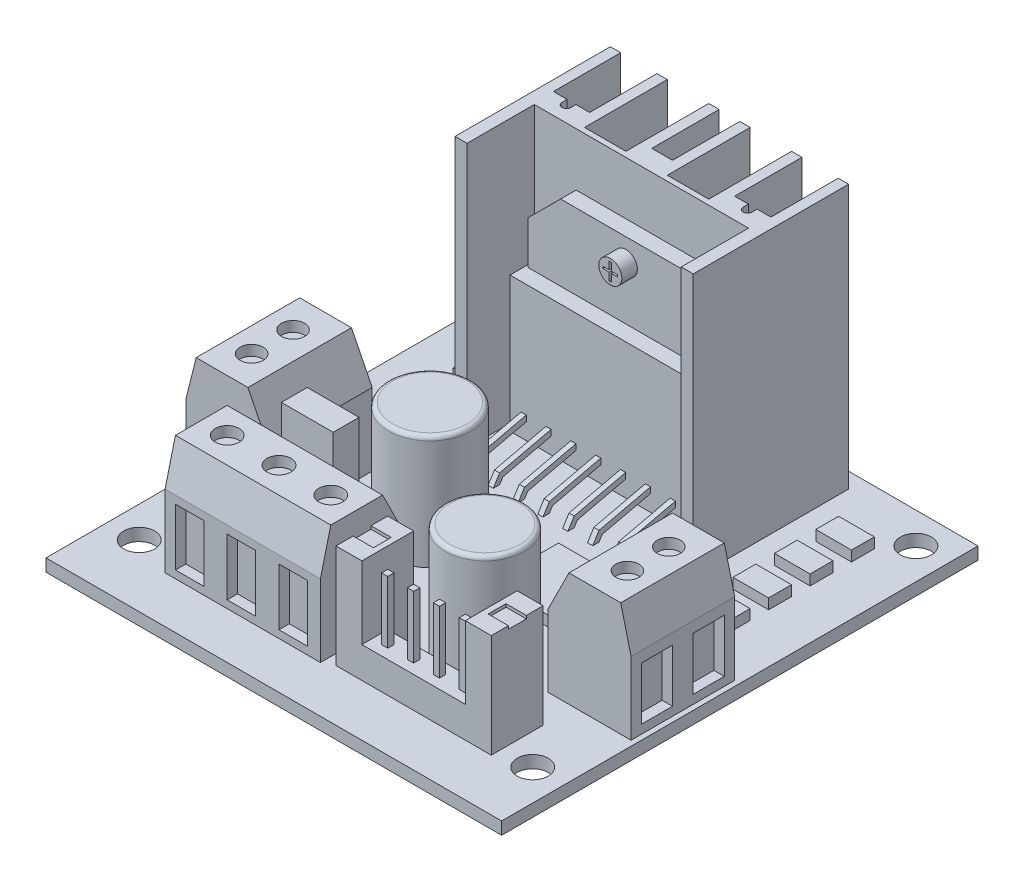
SolidWorks part; units mm, degrees
ref_plane "Alzado" through (0, 0, 0) normal (0, 0, 1) x (1, 0, 0)
ref_plane "Planta" through (0, 0, 0) normal (0, 1, 0) x (1, 0, 0)
ref_plane "Vista lateral" through (0, 0, 0) normal (1, 0, 0) x (0, 0, -1)
sketch "Croquis1" plane through (0, 0, 0) normal (0, 1, 0) x (1, 0, 0)
  line L0 (0, 0) -> (0, -13.9833) construction
  line L1 (-22, 23) -> (22, 23)
  line L2 (-22, 23) -> (-22, -23)
  line L3 (-22, -23) -> (22, -23)
  line L4 (22, 23) -> (22, -23)
  line L5 (-22, 23) -> (22, -23) construction
  line L6 (-22, -23) -> (22, 23) construction
  circle A0 centre (-19, 20) radius 1.5
  circle A1 centre (-19, -17) radius 1.5
  circle A2 centre (19, -17) radius 1.5
  circle A3 centre (19, 20) radius 1.5
  point P0 (0, 0)
  dimension "D3" = 3
  dimension "D5" = 6
  dimension "D1" = 44
  dimension "D2" = 46
  dimension "D4" = 3
  dimension "D6" = 3
extrude "Saliente-Extruir1" add sketch "Croquis1" along normal blind 1.2
sketch "Croquis2" plane through (0, 1.2, 0) normal (0, 1, 0) x (1, 0, 0)
  line L0 (-11, 21.5) -> (-11, 15)
  line L1 (-12, 21.5) -> (-11, 21.5)
  line L2 (-12, 21.5) -> (-12, 6.5)
  line L3 (-12, 6.5) -> (-10.8432, 6.5)
  line L4 (11, 21.5) -> (11, 6.5)
  line L5 (-12, 21.5) -> (11, 6.5) construction
  line L6 (-12, 6.5) -> (11, 21.5) construction
  line L7 (-7.5, 21.5) -> (-7.5, 15)
  line L8 (-6.5, 21.5) -> (-6.5, 13.5)
  line L9 (-2.5, 21.5) -> (-2.5, 13.5)
  line L10 (-1.5, 21.5) -> (-1.5, 15)
  line L11 (-11, 15) -> (-9.6769, 15)
  line L12 (-6.5, 13.5) -> (-2.5, 13.5)
  line L13 (9.8432, 6.5) -> (11, 6.5)
  line L14 (-7.5, 21.5) -> (-7.5, 11.9163) construction
  line L15 (-6.5, 15) -> (-6.0594, 15)
  line L16 (-6.5, 21.5) -> (-6.5, 11.9163) construction
  line L17 (-8.8231, 15) -> (-8.8231, 14.5062)
  line L18 (-9.6769, 15) -> (-9.6769, 14.5062)
  line L19 (-8.8231, 15) -> (-7.5, 15)
  line L20 (-1.5, 21.5) -> (-1.5, 11.9163) construction
  line L21 (-2.5, 21.5) -> (-2.5, 11.9163) construction
  line L22 (-0.5, 14) -> (-0.5, 10.3568) construction
  line L23 (0.5, 21.5) -> (0.5, 15)
  line L24 (1.5, 21.5) -> (1.5, 13.5)
  line L25 (5.5, 13.5) -> (1.5, 13.5)
  line L26 (5.5, 21.5) -> (5.5, 13.5)
  line L27 (8.6769, 15) -> (8.6769, 14.5062)
  line L28 (7.8231, 15) -> (7.8231, 14.5062)
  line L29 (7.8231, 15) -> (6.5, 15)
  line L30 (10, 15) -> (8.6769, 15)
  line L31 (6.5, 21.5) -> (6.5, 15)
  line L32 (10, 21.5) -> (10, 15)
  line L33 (-0.5, 6.5) -> (-0.5, 10) construction
  line L34 (0.5, 15) -> (-1.5, 15)
  line L35 (-10.8432, 7.0064) -> (-10.8432, 6.5)
  line L36 (-10.8432, 12.9936) -> (9.8432, 12.9936)
  line L37 (-10.8432, 12.9936) -> (-10.8432, 7.0064)
  line L39 (9.8432, 12.9936) -> (9.8432, 7.0064)
  line L40 (-10.8432, 12.9936) -> (9.8432, 7.0064) construction
  line L41 (-10.8432, 7.0064) -> (9.8432, 12.9936) construction
  line L42 (9.8432, 7.0064) -> (9.8432, 6.5)
  line L43 (-7.5, 21.5) -> (-6.5, 21.5)
  line L44 (-2.5, 21.5) -> (-1.5, 21.5)
  line L45 (5.5, 21.5) -> (6.5, 21.5)
  line L46 (0.5, 21.5) -> (1.5, 21.5)
  line L47 (10, 21.5) -> (11, 21.5)
  line L48 (22, -23) -> (22, 23) construction
  line L49 (22, 23) -> (-22, 23) construction
  arc A1 (-9.6769, 14.5062) -> (-8.8231, 14.5062) centre (-9.25, 14.5062) ccw
  arc A2 (8.6769, 14.5062) -> (7.8231, 14.5062) centre (8.25, 14.5062) cw
  point P0 (-0.5, 14)
  point P24 (-5.9103, 15.0438)
  dimension "D1" = 15
  dimension "D2" = 23
  dimension "D3" = 1
  dimension "D4" = 3.5
  dimension "D8" = 6.5
  dimension "D9" = 8
  dimension "D10" = 3.5
  dimension "D11" = 11
  dimension "D12" = 1.5
  dimension "D5" = 1
  dimension "D6" = 4
  dimension "D7" = 1
extrude "Saliente-Extruir2" add sketch "Croquis2" along normal blind 25.5 contours L27 A2 L28 L29 L31 L45 L26 L25 L24 L46 L23 L34 L10 L44 L9 L12 L8 L43 L7 L19 L17 A1 L18 L11 L0 L1 L2 L3 L35 L37 L36 L39 L42 L13 L4 L47 L32 L30
sketch "Croquis3" plane through (0, 0, -12.9936) normal (0, 0, 1) x (1, 0, 0)
  line L0 (-10.8432, 7.7335) -> (9.8432, 7.7335)
  line L1 (-10.8432, 26.7) -> (-10.8432, 1.2) construction
  line L2 (9.8432, 26.7) -> (9.8432, 1.2) construction
  line L3 (-10.8432, 1.2) -> (9.8432, 1.2) construction
  line L4 (-10.1827, 14.267) -> (9.1827, 14.267)
  line L5 (-10.1827, 14.267) -> (-10.1827, 1.2)
  line L6 (-10.1827, 1.2) -> (9.1827, 1.2)
  line L7 (9.1827, 14.267) -> (9.1827, 1.2)
  line L8 (-10.1827, 14.267) -> (9.1827, 1.2) construction
  line L9 (-10.1827, 1.2) -> (9.1827, 14.267) construction
  line L10 (-9.9371, 14.267) -> (-9.9371, 18.4293)
  line L11 (-9.9371, 18.4293) -> (-6.8014, 21.565)
  line L12 (-6.8014, 21.565) -> (5.8014, 21.565)
  line L13 (-0.5, 21.565) -> (-0.5, 14.267) construction
  line L14 (8.9371, 14.267) -> (8.9371, 18.4293)
  line L15 (8.9371, 18.4293) -> (5.8014, 21.565)
  point P6 (-0.5, 7.7335)
  line M9 (-10.8432, 1.2) -> (9.8432, 1.2)
extrude "Saliente-Extruir3" add sketch "Croquis3" along normal blind 1.5 contours L14 L15 L12 L11 L10 L4 | L7 L4 L5 L0 | L7 L0 L5 M9
sketch "Croquis4" plane through (0, 0, -11.4936) normal (0, 0, 1) x (1, 0, 0)
  line L0 (-9.9371, 14.267) -> (8.9371, 14.267)
  line L2 (-0.6058, 20.2107) -> (-0.3942, 20.2107)
  line L3 (-0.6058, 20.2107) -> (-0.6058, 18.5641)
  line L4 (-0.6058, 18.5641) -> (-0.3942, 18.5641)
  line L5 (-0.3942, 20.2107) -> (-0.3942, 18.5641)
  line L6 (-0.6058, 20.2107) -> (-0.3942, 18.5641) construction
  line L7 (-0.6058, 18.5641) -> (-0.3942, 20.2107) construction
  line L8 (-1.1956, 19.4768) -> (0.1956, 19.4768)
  line L9 (-1.1956, 19.4768) -> (-1.1956, 19.298)
  line L10 (8.9371, 14.267) -> (8.9371, 18.4293)
  line L11 (8.9371, 18.4293) -> (5.8014, 21.565)
  line L12 (5.8014, 21.565) -> (-6.8014, 21.565)
  line L13 (-6.8014, 21.565) -> (-9.9371, 18.4293)
  line L14 (-9.9371, 18.4293) -> (-9.9371, 14.267)
  line L15 (-9.9371, 14.267) -> (-10.1827, 14.267)
  line L16 (-10.1827, 14.267) -> (-10.1827, 1.2)
  line L17 (-10.1827, 1.2) -> (9.1827, 1.2)
  line L18 (9.1827, 1.2) -> (9.1827, 14.267)
  line L19 (9.1827, 14.267) -> (8.9371, 14.267)
  line L25 (-9.9371, 14.267) -> (-10.1827, 14.267)
  line L26 (-10.1827, 14.267) -> (-10.1827, 1.2)
  line L27 (-10.1827, 1.2) -> (9.1827, 1.2)
  line L28 (9.1827, 1.2) -> (9.1827, 14.267)
  line L29 (9.1827, 14.267) -> (8.9371, 14.267)
  line L30 (-1.1956, 19.298) -> (0.1956, 19.298)
  line L31 (0.1956, 19.4768) -> (0.1956, 19.298)
  line L32 (-1.1956, 19.4768) -> (0.1956, 19.298) construction
  line L33 (-1.1956, 19.298) -> (0.1956, 19.4768) construction
  circle A0 centre (-0.5, 19.3874) radius 1.1143
  line M16 (-9.9371, 14.267) -> (-10.1827, 14.267)
  line M17 (-10.1827, 14.267) -> (-10.1827, 1.2)
  line M18 (-10.1827, 1.2) -> (9.1827, 1.2)
  line M19 (9.1827, 1.2) -> (9.1827, 14.267)
  line M20 (9.1827, 14.267) -> (8.9371, 14.267)
  dimension "D1" = 0
extrude "Saliente-Extruir4" add sketch "Croquis4" along normal blind 1.5 contours L0 M16 M17 M18 M19 M20 | A0 L8 L31 L30 L5 L4 L3 L9 L2
ref_plane "Plano1" through (7.9327, 0, 0) normal (1, 0, 0) x (0, 0, -1)
sketch "Croquis6" plane through (7.9327, 0, 0) normal (1, 0, 0) x (0, 0, -1)
  line L0 (9.9936, 3.3424) -> (5.0225, 2.1849)
  line L1 (9.9936, 14.267) -> (9.9936, 1.2) construction
  line L2 (5.0225, 2.1849) -> (4.4097, 1.2)
  line L3 (23, 1.2) -> (-23, 1.2) construction
  line L4 (4.4097, 1.2) -> (5.0225, 1.2)
  line L5 (5.0225, 1.2) -> (5.329, 1.6924)
  line L6 (5.329, 1.6924) -> (9.9936, 2.7786)
  line L7 (9.9936, 2.7786) -> (9.9936, 3.3424)
extrude "Saliente-Extruir5" add sketch "Croquis6" along normal blind 0.25 and the other way blind 0.25
pattern_linear "MatrizL1" count 8 spacing 2.4 along (-1, 0, 0) of "Saliente-Extruir5"
sketch "Croquis7" plane through (0, 1.2, 0) normal (0, 1, 0) x (1, 0, 0)
  line L0 (-17.2352, 13.7523) -> (-13.7882, 11.5462) construction
  line L1 (-17.2352, 17.7523) -> (-13.7882, 17.7523)
  line L2 (-17.2352, 17.7523) -> (-17.2352, 15.5462)
  line L3 (-17.2352, 15.5462) -> (-13.7882, 15.5462)
  line L4 (-13.7882, 17.7523) -> (-13.7882, 15.5462)
  line L5 (-17.2352, 17.7523) -> (-13.7882, 15.5462) construction
  line L6 (-17.2352, 15.5462) -> (-13.7882, 17.7523) construction
  line L7 (-17.2352, 11.5462) -> (-13.7882, 13.7523) construction
  line L8 (-17.2352, 13.7523) -> (-17.2352, 11.5462)
  line L9 (-17.2352, 13.7523) -> (-13.7882, 13.7523)
  line L10 (-13.7882, 13.7523) -> (-13.7882, 11.5462)
  line L11 (-17.2352, 11.5462) -> (-13.7882, 11.5462)
  line L12 (-17.2352, 9.7523) -> (-13.7882, 7.5462) construction
  line L13 (-17.2352, 7.5462) -> (-13.7882, 9.7523) construction
  line L14 (-17.2352, 9.7523) -> (-17.2352, 7.5462)
  line L15 (-17.2352, 9.7523) -> (-13.7882, 9.7523)
  line L16 (-13.7882, 9.7523) -> (-13.7882, 7.5462)
  line L17 (-17.2352, 7.5462) -> (-13.7882, 7.5462)
  line L18 (-17.2352, 5.7523) -> (-13.7882, 3.5462) construction
  line L19 (-17.2352, 3.5462) -> (-13.7882, 5.7523) construction
  line L20 (-17.2352, 5.7523) -> (-17.2352, 3.5462)
  line L21 (-17.2352, 5.7523) -> (-13.7882, 5.7523)
  line L22 (-13.7882, 5.7523) -> (-13.7882, 3.5462)
  line L23 (-17.2352, 3.5462) -> (-13.7882, 3.5462)
  line L24 (0, 0) -> (0, -5.3512) construction
  line L25 (17.2352, 3.5462) -> (13.7882, 5.7523) construction
  line L26 (17.2352, 5.7523) -> (13.7882, 3.5462) construction
  line L27 (17.2352, 7.5462) -> (13.7882, 9.7523) construction
  line L28 (17.2352, 9.7523) -> (13.7882, 7.5462) construction
  line L29 (17.2352, 11.5462) -> (13.7882, 13.7523) construction
  line L30 (17.2352, 15.5462) -> (13.7882, 17.7523) construction
  line L31 (17.2352, 17.7523) -> (13.7882, 15.5462) construction
  line L32 (17.2352, 13.7523) -> (13.7882, 11.5462) construction
  line L33 (17.2352, 3.5462) -> (13.7882, 3.5462)
  line L34 (13.7882, 5.7523) -> (13.7882, 3.5462)
  line L35 (17.2352, 5.7523) -> (13.7882, 5.7523)
  line L36 (17.2352, 5.7523) -> (17.2352, 3.5462)
  line L37 (17.2352, 7.5462) -> (13.7882, 7.5462)
  line L38 (13.7882, 9.7523) -> (13.7882, 7.5462)
  line L39 (17.2352, 9.7523) -> (13.7882, 9.7523)
  line L40 (17.2352, 9.7523) -> (17.2352, 7.5462)
  line L41 (17.2352, 11.5462) -> (13.7882, 11.5462)
  line L42 (13.7882, 13.7523) -> (13.7882, 11.5462)
  line L43 (17.2352, 13.7523) -> (13.7882, 13.7523)
  line L44 (17.2352, 13.7523) -> (17.2352, 11.5462)
  line L45 (13.7882, 17.7523) -> (13.7882, 15.5462)
  line L46 (17.2352, 15.5462) -> (13.7882, 15.5462)
  line L47 (17.2352, 17.7523) -> (17.2352, 15.5462)
  line L48 (17.2352, 17.7523) -> (13.7882, 17.7523)
  line L50 (2.5023, 1.9928) -> (8.2995, 1.9928)
  line L51 (2.5023, 1.9928) -> (2.5023, -4.5399)
  line L52 (2.5023, -4.5399) -> (8.2995, -4.5399)
  line L53 (8.2995, 1.9928) -> (8.2995, -4.5399)
  line L54 (2.5023, 1.9928) -> (8.2995, -4.5399) construction
  line L55 (2.5023, -4.5399) -> (8.2995, 1.9928) construction
  point P0 (-15.5117, 16.6492)
  point P7 (-15.5117, 12.6492)
  point P12 (-15.5117, 8.6492)
  point P17 (-15.5117, 4.6492)
  point P39 (15.5117, 4.6492)
  point P40 (15.5117, 8.6492)
  point P41 (15.5117, 12.6492)
  point P42 (15.5117, 16.6492)
  point P43 (5.4009, -1.2736)
  dimension "D1" = 4
extrude "Saliente-Extruir6" add sketch "Croquis7" along normal blind 1
sketch "Croquis8" plane through (0, 1.2, 0) normal (0, 1, 0) x (1, 0, 0)
  line L0 (-22, 23) -> (-22, -23) construction
  line L1 (-21.5, 0) -> (-13.5, 0)
  line L2 (-21.5, 0) -> (-21.5, -10)
  line L3 (-21.5, -10) -> (-13.5, -10)
  line L4 (-13.5, 0) -> (-13.5, -10)
  line L5 (-21.5, 0) -> (-13.5, -10) construction
  line L6 (-21.5, -10) -> (-13.5, 0) construction
  line L7 (-22, -23) -> (22, -23) construction
  point P0 (-17.5, -5)
  dimension "D1" = 10
  dimension "D2" = 8
  dimension "D3" = 0.5
  dimension "D4" = 13
extrude "Saliente-Extruir7" add sketch "Croquis8" along normal blind 11
sketch "Croquis9" plane through (0, 0, 10) normal (0, 0, 1) x (1, 0, 0)
  line L0 (-21.5, 8.2) -> (-20.5, 12.2)
  line L1 (-15.5, 12.2) -> (-13.5, 8.2)
  line L2 (-20.5, 12.2) -> (-21.5, 12.2)
  line L4 (-21.5, 1.2) -> (-13.5, 1.2)
  line L5 (-13.5, 1.2) -> (-13.5, 12.2)
  line L6 (-13.5, 12.2) -> (-21.5, 12.2)
  line L7 (-21.5, 12.2) -> (-21.5, 1.2)
  line L9 (-13.5, 8.2) -> (-13.5, 12.2)
  line L10 (-13.5, 12.2) -> (-15.5, 12.2)
  line L11 (-21.5, 12.2) -> (-21.5, 8.2)
  dimension "D2" = 4
  dimension "D3" = 5
  dimension "D4" = 1
  dimension "D5" = 4
  dimension "D1" = 0
extrude "Cortar-Extruir1" cut sketch "Croquis9" against normal blind 11
sketch "Croquis10" plane through (0, 12.2, 0) normal (0, 1, 0) x (1, 0, 0)
  line L0 (-15.5, 0) -> (-20.5, 0) construction
  circle A0 centre (-18.1447, -3) radius 1.111
  circle A3 centre (-18.1447, -7) radius 1.111
  dimension "D1" = 3
  dimension "D2" = 2
extrude "Cortar-Extruir2" cut sketch "Croquis10" against normal blind 1
sketch "Croquis11" plane through (-21.5, 0, 0) normal (-1, 0, 0) x (0, 0, 1)
  line L0 (0, 8.2) -> (0, 1.2) construction
  line L1 (1, 7.1567) -> (4, 7.1567)
  line L2 (1, 7.1567) -> (1, 2.0425)
  line L3 (1, 2.0425) -> (4, 2.0425)
  line L4 (4, 7.1567) -> (4, 2.0425)
  line L5 (1, 7.1567) -> (4, 2.0425) construction
  line L6 (1, 2.0425) -> (4, 7.1567) construction
  line L7 (6, 7.1567) -> (6, 2.0425)
  line L8 (6, 7.1567) -> (9, 7.1567)
  line L9 (9, 7.1567) -> (9, 2.0425)
  line L10 (6, 2.0425) -> (9, 2.0425)
  point P0 (2.5, 4.5996)
  dimension "D1" = 1
  dimension "D2" = 3
  dimension "D3" = 2
extrude "Cortar-Extruir3" cut sketch "Croquis11" against normal blind 1
mirror "Simetría1" about plane through (0, 0, 0) normal (1, 0, 0) of "Saliente-Extruir7", "Cortar-Extruir1", "Cortar-Extruir2", "Cortar-Extruir3"
sketch "Croquis12" plane through (0, 1.2, 0) normal (0, 1, 0) x (1, 0, 0)
  line L0 (-22, -23) -> (22, -23) construction
  line L1 (-15, -10.5) -> (0, -10.5)
  line L2 (-15, -10.5) -> (-15, -18.5)
  line L3 (-15, -18.5) -> (0, -18.5)
  line L4 (0, -10.5) -> (0, -18.5)
  line L5 (-15, -10.5) -> (0, -18.5) construction
  line L6 (-15, -18.5) -> (0, -10.5) construction
  line L7 (-22, 23) -> (-22, -23) construction
  point P0 (-7.5, -14.5)
  dimension "D1" = 15
  dimension "D2" = 8
  dimension "D3" = 4.5
  dimension "D4" = 7
extrude "Saliente-Extruir8" add sketch "Croquis12" along normal blind 11
sketch "Croquis13" plane through (0, 0, 0) normal (1, 0, 0) x (0, 0, -1)
  line L0 (-18.5, 8.2) -> (-17.5, 12.2)
  line L1 (-12.5, 12.2) -> (-10.5, 8.2)
  line L3 (-17.5, 12.2) -> (-18.5, 12.2)
  line L4 (-18.5, 1.2) -> (-10.5, 1.2)
  line L5 (-10.5, 1.2) -> (-10.5, 12.2)
  line L6 (-10.5, 12.2) -> (-18.5, 12.2)
  line L7 (-18.5, 12.2) -> (-18.5, 1.2)
  line L9 (-10.5, 8.2) -> (-10.5, 12.2)
  line L10 (-10.5, 12.2) -> (-12.5, 12.2)
  line L11 (-18.5, 12.2) -> (-18.5, 8.2)
  dimension "D2" = 4
  dimension "D3" = 4
  dimension "D4" = 5
  dimension "D5" = 1
  dimension "D1" = 0
extrude "Cortar-Extruir4" cut sketch "Croquis13" against normal blind 15
sketch "Croquis14" plane through (0, 12.2, 0) normal (0, 1, 0) x (1, 0, 0)
  line L0 (-15, -12.5) -> (-15, -17.5) construction
  line L1 (-15, -12.5) -> (0, -12.5) construction
  circle A0 centre (-12.5, -15) radius 1.1533
  circle A1 centre (-7.5, -15) radius 1.1533
  circle A2 centre (-2.5, -15) radius 1.1533
  dimension "D1" = 2.5
  dimension "D3" = 2.5
  dimension "D2" = 3
extrude "Cortar-Extruir5" cut sketch "Croquis14" against normal blind 1
sketch "Croquis15" plane through (0, 0, 18.5) normal (0, 0, 1) x (1, 0, 0)
  line L0 (-15, 8.2) -> (-15, 1.2) construction
  line L1 (-14, 7.4419) -> (-11.2484, 7.4419)
  line L2 (-14, 7.4419) -> (-14, 1.9387)
  line L3 (-14, 1.9387) -> (-11.2484, 1.9387)
  line L4 (-11.2484, 7.4419) -> (-11.2484, 1.9387)
  line L5 (-14, 7.4419) -> (-11.2484, 1.9387) construction
  line L6 (-14, 1.9387) -> (-11.2484, 7.4419) construction
  line L7 (-9, 7.4419) -> (-9, 1.9387)
  line L8 (-9, 7.4419) -> (-6.2484, 7.4419)
  line L9 (-6.2484, 7.4419) -> (-6.2484, 1.9387)
  line L10 (-9, 1.9387) -> (-6.2484, 1.9387)
  line L11 (-4, 7.4419) -> (-4, 1.9387)
  line L12 (-4, 7.4419) -> (-1.2484, 7.4419)
  line L13 (-1.2484, 7.4419) -> (-1.2484, 1.9387)
  line L14 (-4, 1.9387) -> (-1.2484, 1.9387)
  point P0 (-12.6242, 4.6903)
  dimension "D1" = 1
  dimension "D2" = 3
extrude "Cortar-Extruir6" cut sketch "Croquis15" against normal blind 1
sketch "Croquis16" plane through (0, 1.2, 0) normal (0, 1, 0) x (1, 0, 0)
  line L0 (-22, -23) -> (22, -23) construction
  line L1 (1, -15.5) -> (16, -15.5)
  line L2 (1, -15.5) -> (1, -18)
  line L3 (1, -18) -> (16, -18)
  line L4 (16, -15.5) -> (16, -18)
  line L5 (1, -15.5) -> (16, -18) construction
  line L6 (1, -18) -> (16, -15.5) construction
  line L7 (22, -23) -> (22, 23) construction
  point P0 (8.5, -16.75)
  point P7 (16, -16.75)
  dimension "D1" = 2.5
  dimension "D2" = 15
  dimension "D3" = 5
  dimension "D4" = 6
extrude "Saliente-Extruir9" add sketch "Croquis16" along normal blind 3
sketch "Croquis17" plane through (0, 4.2, 0) normal (0, 1, 0) x (1, 0, 0)
  line L0 (1, -15.5) -> (1, -18) construction
  line L1 (1.95, -16.45) -> (2.55, -16.45)
  line L2 (1.95, -16.45) -> (1.95, -17.05)
  line L3 (1.95, -17.05) -> (2.55, -17.05)
  line L4 (2.55, -16.45) -> (2.55, -17.05)
  line L5 (1.95, -16.45) -> (2.55, -17.05) construction
  line L6 (1.95, -17.05) -> (2.55, -16.45) construction
  line L9 (1, -18) -> (16, -18) construction
  line L10 (4.45, -16.45) -> (4.45, -17.05)
  line L11 (4.45, -16.45) -> (5.05, -16.45)
  line L12 (5.05, -16.45) -> (5.05, -17.05)
  line L13 (4.45, -17.05) -> (5.05, -17.05)
  line L14 (6.95, -16.45) -> (6.95, -17.05)
  line L15 (6.95, -16.45) -> (7.55, -16.45)
  line L16 (7.55, -16.45) -> (7.55, -17.05)
  line L17 (6.95, -17.05) -> (7.55, -17.05)
  line L18 (9.45, -16.45) -> (9.45, -17.05)
  line L19 (9.45, -16.45) -> (10.05, -16.45)
  line L20 (10.05, -16.45) -> (10.05, -17.05)
  line L21 (9.45, -17.05) -> (10.05, -17.05)
  line L22 (11.95, -16.45) -> (11.95, -17.05)
  line L23 (11.95, -16.45) -> (12.55, -16.45)
  line L24 (12.55, -16.45) -> (12.55, -17.05)
  line L25 (11.95, -17.05) -> (12.55, -17.05)
  line L26 (14.45, -16.45) -> (14.45, -17.05)
  line L27 (14.45, -16.45) -> (15.05, -16.45)
  line L28 (15.05, -16.45) -> (15.05, -17.05)
  line L29 (14.45, -17.05) -> (15.05, -17.05)
  point P0 (2.25, -16.75)
  dimension "D1" = 0.6
  dimension "D2" = 0.6
  dimension "D3" = 1.25
  dimension "D4" = 1.25
  dimension "D5" = 6
extrude "Saliente-Extruir10" add sketch "Croquis17" along normal blind 6
sketch "Croquis18" plane through (0, 4.2, 0) normal (0, 1, 0) x (1, 0, 0)
  line L0 (8.5, -15.5) -> (8.5, -12.7352) construction
  line L2 (16, -15.5) -> (1, -15.5) construction
  line L3 (1, -18) -> (3.5, -18)
  line L4 (1, -18) -> (1, -13)
  line L5 (1, -13) -> (3.5, -13)
  line L6 (3.5, -18) -> (3.5, -13)
  line L7 (16, -13) -> (13.5, -13)
  line L8 (13.5, -18) -> (13.5, -13)
  line L9 (16, -18) -> (13.5, -18)
  line L10 (16, -18) -> (16, -13)
  dimension "D1" = 2.5
  dimension "D2" = 5
extrude "Saliente-Extruir11" add sketch "Croquis18" along normal blind 7 and the other way up to surface
sketch "Croquis19" plane through (0, 11.2, 0) normal (0, 1, 0) x (1, 0, 0)
  line L0 (1, -13) -> (1, -18) construction
  line L1 (1, -14.6159) -> (2.9611, -14.6159)
  line L2 (1, -14.6159) -> (1, -16.3434)
  line L3 (1, -16.3434) -> (2.9611, -16.3434)
  line L4 (2.9611, -14.6159) -> (2.9611, -16.3434)
  line L5 (8.5, -15.5) -> (8.5, -12.6004) construction
  line L6 (13.5, -15.5) -> (3.5, -15.5) construction
  line L7 (16, -16.3434) -> (14.0389, -16.3434)
  line L8 (14.0389, -14.6159) -> (14.0389, -16.3434)
  line L9 (16, -14.6159) -> (14.0389, -14.6159)
  line L10 (16, -14.6159) -> (16, -16.3434)
extrude "Cortar-Extruir7" cut sketch "Croquis19" against normal blind 0.3
sketch "Croquis20" plane through (0, 1.2, 0) normal (0, 1, 0) x (1, 0, 0)
  line L1 (-12.6382, -7.132) -> (-7.6382, -7.132)
  line L2 (-12.6382, -7.132) -> (-12.6382, -9.632)
  line L3 (-12.6382, -9.632) -> (-7.6382, -9.632)
  line L4 (-7.6382, -7.132) -> (-7.6382, -9.632)
  line L5 (-12.6382, -7.132) -> (-7.6382, -9.632) construction
  line L6 (-12.6382, -9.632) -> (-7.6382, -7.132) construction
  circle A0 centre (-5.4601, -2.4646) radius 3.9913
  circle A1 centre (7.356, -9.9723) radius 3.8107
  point P4 (-10.1382, -8.382)
  dimension "D1" = 5
  dimension "D2" = 2.5
extrude "Saliente-Extruir12" add sketch "Croquis20" along normal blind 11
fillet "Redondeo1" radius 0.4 2 edges at (7.356, 12.2, 13.783) (-5.4601, 12.2, 6.4559)
